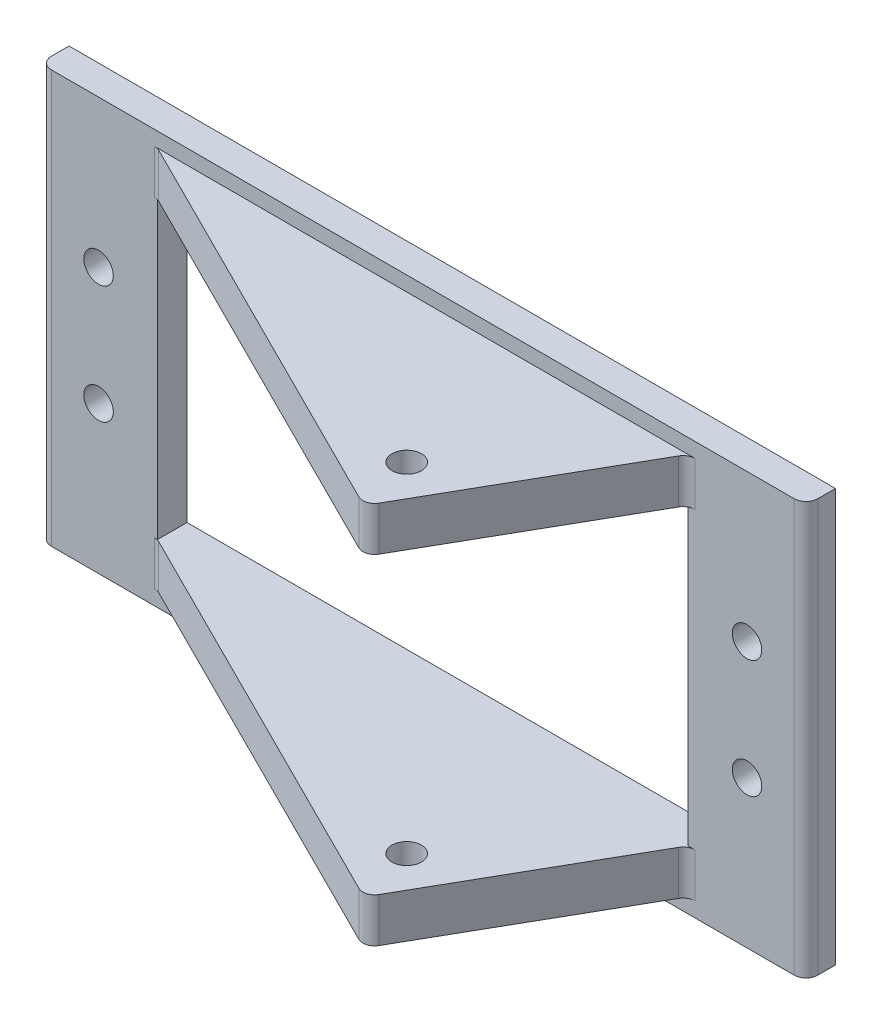
SolidWorks part; units mm, degrees
material "6061-T6 (SS)"
ref_plane "Front Plane" through (0, 0, 0) normal (0, 0, 1) x (1, 0, 0)
ref_plane "Top Plane" through (0, 0, 0) normal (0, 1, 0) x (1, 0, 0)
ref_plane "Right Plane" through (0, 0, 0) normal (1, 0, 0) x (0, 0, -1)
sketch "Sketch1" plane through (0, 0, 0) normal (0, 0, 1) x (1, 0, 0)
  line L1 (-82.55, 44.45) -> (82.55, 44.45)
  line L2 (-82.55, 44.45) -> (-82.55, -44.45)
  line L3 (-82.55, -44.45) -> (82.55, -44.45)
  line L4 (82.55, 44.45) -> (82.55, -44.45)
  line L5 (-82.55, 44.45) -> (82.55, -44.45) construction
  line L6 (-82.55, -44.45) -> (82.55, 44.45) construction
  point P0 (0, 0)
  dimension "D1" = 165.1
  dimension "D2" = 88.9
extrude "Boss-Extrude1" add sketch "Sketch1" along normal blind 50.8
sketch "Sketch2" plane through (0, 0, 50.8) normal (0, 0, 1) x (1, 0, 0)
  line L0 (-82.55, 0) -> (82.55, 0) construction
  line L1 (82.55, -44.45) -> (82.55, 44.45) construction
  line L2 (0, 0) -> (0, -31.75) construction
  line L3 (-57.15, 31.75) -> (57.15, 31.75)
  line L4 (-57.15, 31.75) -> (-57.15, -31.75)
  line L5 (-57.15, -31.75) -> (57.15, -31.75)
  line L6 (57.15, 31.75) -> (57.15, -31.75)
  line L7 (-57.15, 31.75) -> (57.15, -31.75) construction
  line L8 (-57.15, -31.75) -> (57.15, 31.75) construction
  circle A0 centre (-69.85, 12.7) radius 3.175
  circle A1 centre (-69.85, -12.7) radius 3.175
  circle A2 centre (69.85, -12.7) radius 3.175
  circle A3 centre (69.85, 12.7) radius 3.175
  point P0 (0, 0)
  point P6 (0, 0)
  dimension "D3" = 6.35
  dimension "D1" = 114.3
  dimension "D2" = 63.5
  dimension "D4" = 12.7
  dimension "D5" = 12.7
extrude "Cut-Extrude1" cut sketch "Sketch2" against normal through all
ref_plane "Plane1" through (0, -40.64, 0) normal (0, -1, 0) x (-1, 0, 0)
ref_plane "Plane2" through (0, 1.905, 0) normal (0, -1, 0) x (-1, 0, 0)
ref_plane "Plane3" through (0, 40.64, 0) normal (0, 1, 0) x (1, 0, 0)
sketch "Sketch3" plane through (0, 0, 0) normal (0, 0, -1) x (-1, 0, 0)
  line L1 (-57.15, 38.1) -> (57.15, 38.1)
  line L2 (-57.15, 38.1) -> (-57.15, -38.1)
  line L3 (-57.15, -38.1) -> (57.15, -38.1)
  line L4 (57.15, 38.1) -> (57.15, -38.1)
  line L5 (-57.15, 38.1) -> (57.15, -38.1) construction
  line L6 (-57.15, -38.1) -> (57.15, 38.1) construction
  point P0 (0, 0)
  dimension "D1" = 76.2
sketch "Sketch4" plane through (0, 0, 50.8) normal (0, 0, 1) x (1, 0, 0)
  line L1 (82.55, 44.45) -> (-82.55, 44.45)
  line L2 (82.55, 44.45) -> (82.55, -44.45)
  line L3 (82.55, -44.45) -> (-82.55, -44.45)
  line L4 (-82.55, 44.45) -> (-82.55, -44.45)
  line L5 (82.55, 44.45) -> (-82.55, -44.45) construction
  line L6 (82.55, -44.45) -> (-82.55, 44.45) construction
  line L7 (57.15, 41.275) -> (-57.15, 41.275)
  line L8 (57.15, 41.275) -> (57.15, -41.275)
  line L9 (57.15, -41.275) -> (-57.15, -41.275)
  line L10 (-57.15, 41.275) -> (-57.15, -41.275)
  line L11 (57.15, 41.275) -> (-57.15, -41.275) construction
  line L12 (57.15, -41.275) -> (-57.15, 41.275) construction
  point P0 (0, 0)
  point P7 (0, 0)
  dimension "D1" = 82.55
  dimension "D2" = 114.3
extrude "Cut-Extrude2" cut sketch "Sketch4" against normal blind 44.45
sketch "Sketch5" plane through (0, -41.275, 0) normal (0, -1, 0) x (1, 0, 0)
  line L0 (0, 0) -> (31.75, 0) construction
  line L1 (-82.55, 0) -> (82.55, 0) construction
  line L2 (31.75, 35.4766) -> (31.75, 50.8) construction
  line L3 (31.75, 0) -> (31.75, 6.35) construction
  line L4 (-57.15, 50.8) -> (57.15, 50.8) construction
  line L6 (-57.15, 0) -> (31.75, 0) construction
  line L7 (57.15, 6.35) -> (31.75, 50.8)
  line L8 (31.75, 50.8) -> (-57.15, 6.35)
  line L12 (27.1461, 33.9189) -> (31.75, 50.8) construction
  line L13 (57.15, 6.35) -> (57.15, 50.8)
  line L14 (57.15, 50.8) -> (-57.15, 50.8)
  line L15 (-57.15, 50.8) -> (-57.15, 6.35)
  circle A0 centre (28.2864, 38.1) radius 3.175
  line M7 (57.15, 50.8) -> (-57.15, 50.8)
  line M8 (-57.15, 50.8) -> (-57.15, 6.35)
  line M10 (57.15, 6.35) -> (57.15, 50.8)
  dimension "D6" = 6.35
  dimension "D1" = 31.75
  dimension "D2" = 88.9
  dimension "D3" = 45
  dimension "D4" = 12.7
extrude "Cut-Extrude4" cut sketch "Sketch5" against normal through all contours L8 M7 M8 | L7 M10 M7 | A0
fillet "Fillet2" radius 2.54 8 edges at (82.55, 0, 6.35) (57.15, 36.5125, 6.35) (57.15, -36.5125, 6.35) (31.75, -36.5125, 50.8) (31.75, 36.5125, 50.8) (-57.15, -36.5125, 6.35) (-57.15, 36.5125, 6.35) (-82.55, 0, 6.35)
